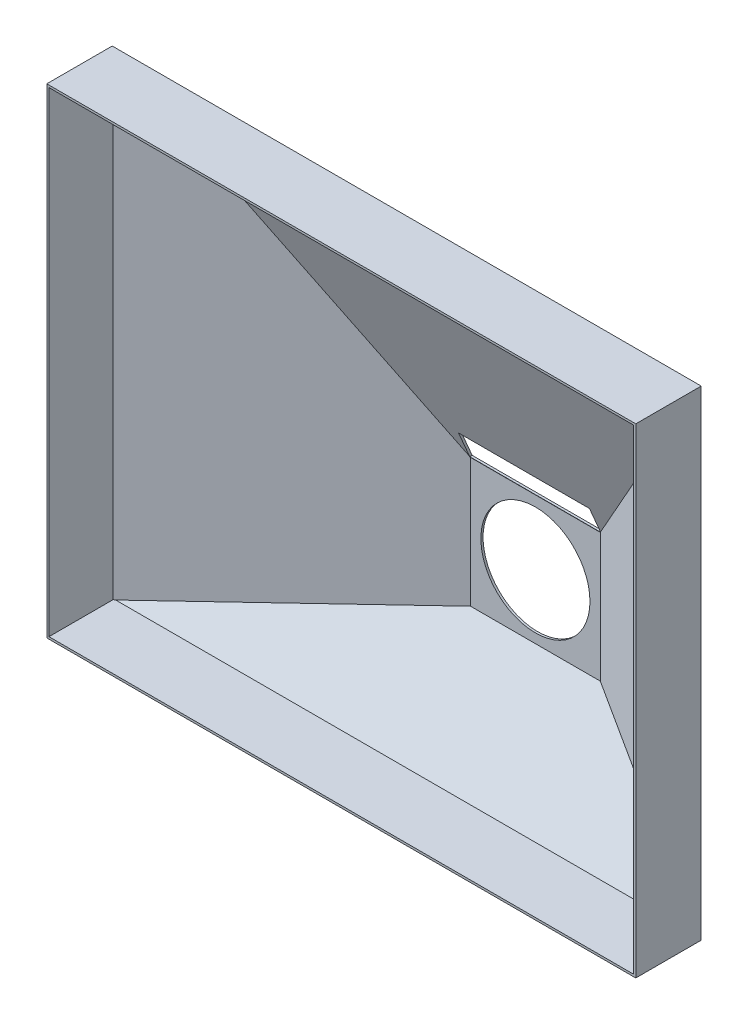
SolidWorks part; units mm, degrees
ref_plane "前视基准面" through (0, 0, 0) normal (0, 0, 1) x (1, 0, 0)
ref_plane "上视基准面" through (0, 0, 0) normal (0, 1, 0) x (1, 0, 0)
ref_plane "右视基准面" through (0, 0, 0) normal (1, 0, 0) x (0, 0, -1)
sketch "草图1" plane through (0, 0, 0) normal (0, 0, 1) x (1, 0, 0)
  line L1 (-30, 30) -> (30, 30)
  line L2 (-30, 30) -> (-30, -30)
  line L3 (-30, -30) -> (30, -30)
  line L4 (30, 30) -> (30, -30)
  line L5 (-30, 30) -> (30, -30) construction
  line L6 (-30, -30) -> (30, 30) construction
  point P0 (0, 0)
  dimension "D1" = 60
ref_plane "基准面1" through (0, 0, 60) normal (0, 0, 1) x (1, 0, 0)
sketch "草图2" plane through (0, 0, 60) normal (0, 0, 1) x (1, 0, 0)
  line L1 (-135, 170) -> (135, 170)
  line L2 (-135, 170) -> (-135, -50)
  line L3 (-135, -50) -> (135, -50)
  line L4 (135, 170) -> (135, -50)
  line L5 (-135, 170) -> (135, -50) construction
  line L6 (-135, -50) -> (135, 170) construction
  point P0 (0, 60)
  dimension "D1" = 270
  dimension "D2" = 220
  dimension "D3" = 60
ref_plane "基准面3" through (0, 0, 90) normal (0, 0, 1) x (1, 0, 0)
loft "放样1" add profiles "草图2", "草图1"
ref_plane "基准面4" through (0, 0, 90) normal (0, 0, 1) x (1, 0, 0)
sketch "草图7" plane through (0, 0, 90) normal (0, 0, 1) x (1, 0, 0)
  line L4 (135, -50) -> (135, 170)
  line L5 (135, 170) -> (-135, 170)
  line L6 (-135, 170) -> (-135, -50)
  line L7 (-135, -50) -> (135, -50)
  line L8 (135, -50) -> (135, 170)
  line L9 (135, 170) -> (-135, 170)
  line L10 (-135, 170) -> (-135, -50)
  line L11 (-135, -50) -> (135, -50)
  dimension "D1" = 0
extrude "凸台-拉伸1" add sketch "草图7" against normal up to next
shell "抽壳1" thickness 1
sketch "草图8" plane through (0, 0, 1) normal (0, 0, 1) x (1, 0, 0)
  circle A0 centre (0, 0) radius 25
  dimension "D1" = 50
extrude "切除-拉伸2" cut sketch "草图8" against normal blind 10
sketch "草图9" plane through (0, 0, 0) normal (0, 0, -1) x (-1, 0, 0)
  line L1 (-30, 30) -> (30, 30)
  line L2 (-30, 30) -> (-30, 42)
  line L3 (-30, 42) -> (30, 42)
  line L4 (30, 30) -> (30, 42)
  point P5 (30, 30)
  dimension "D1" = 12
extrude "切除-拉伸3" cut sketch "草图9" against normal blind 10
